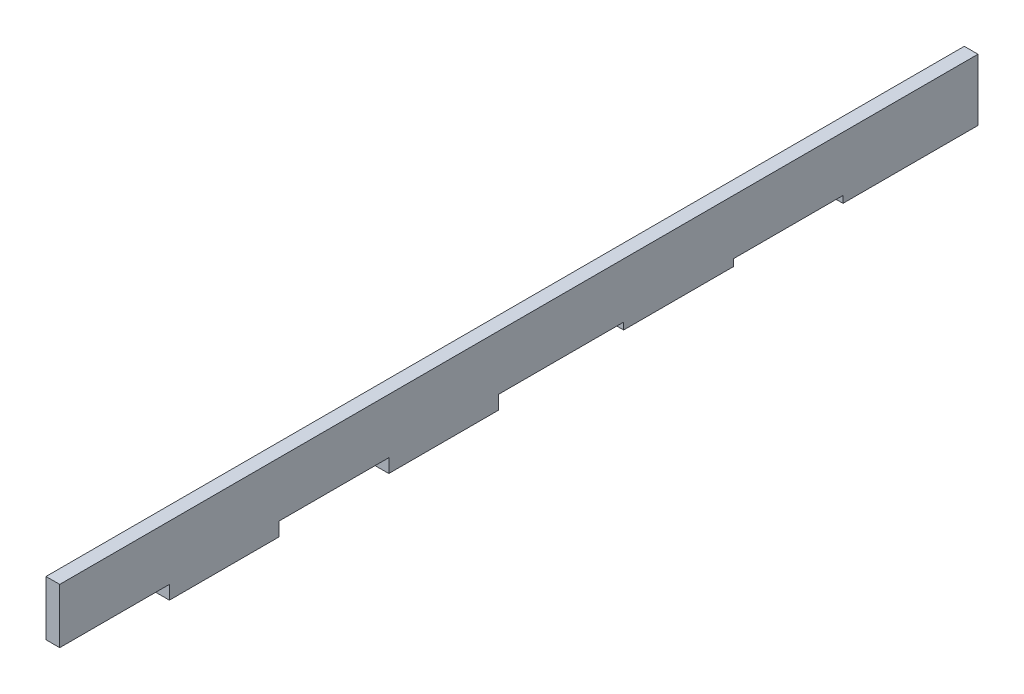
SolidWorks part; units mm, degrees
ref_plane "Front Plane" through (0, 0, 0) normal (0, 0, 1) x (1, 0, 0)
ref_plane "Top Plane" through (0, 0, 0) normal (0, 1, 0) x (1, 0, 0)
ref_plane "Right Plane" through (0, 0, 0) normal (1, 0, 0) x (0, 0, -1)
sketch "Sketch2" plane through (0, 0, 0) normal (1, 0, 0) x (0, 0, -1)
  line L0 (227.5194, 6.35) -> (258.6794, 6.35)
  line L6 (258.6794, 3.175) -> (309.4794, 3.175)
  line L7 (309.4794, 3.175) -> (309.4794, 6.35)
  line L8 (309.4794, 6.35) -> (360.2794, 6.35)
  line L9 (360.2794, 6.35) -> (360.2794, 3.175)
  line L10 (360.2794, 3.175) -> (422.7895, 3.175)
  line L11 (258.6794, 6.35) -> (258.6794, 3.175)
  line L30 (48.3194, 0) -> (99.1194, 0)
  line L31 (-2.4806, 6.35) -> (-2.4806, 31.75)
  line L32 (-2.4806, 31.75) -> (422.7895, 31.75)
  line L33 (422.7895, 3.175) -> (422.7895, 31.75)
  line L38 (200.7194, 6.35) -> (227.5194, 6.35) construction
  line L39 (200.7194, 6.35) -> (200.7194, 0) construction
  line L40 (149.9194, 6.35) -> (149.9194, 0) construction
  line L41 (99.1194, 6.35) -> (149.9194, 6.35) construction
  line L42 (99.1194, 6.35) -> (99.1194, 0) construction
  line L43 (48.3194, 6.35) -> (48.3194, 0) construction
  line L44 (-2.4806, 6.35) -> (48.3194, 6.35) construction
  line L45 (422.7895, 31.75) -> (422.7895, 35.3357) construction
  line L50 (200.7194, 6.35) -> (227.5194, 6.35)
  line L51 (200.7194, 6.35) -> (200.7194, 0)
  line L52 (149.9194, 6.35) -> (149.9194, 0)
  line L53 (99.1194, 6.35) -> (149.9194, 6.35)
  line L54 (99.1194, 6.35) -> (99.1194, 0)
  line L55 (48.3194, 6.35) -> (48.3194, 0)
  line L56 (-2.4806, 6.35) -> (48.3194, 6.35)
  line L59 (149.9194, 0) -> (200.7194, 0)
  dimension "D1" = 3.175
  dimension "D2" = 50.8
  dimension "D3" = 50.8
  dimension "D4" = 3.175
extrude "Boss-Extrude1" add sketch "Sketch2" along normal blind 6.35
